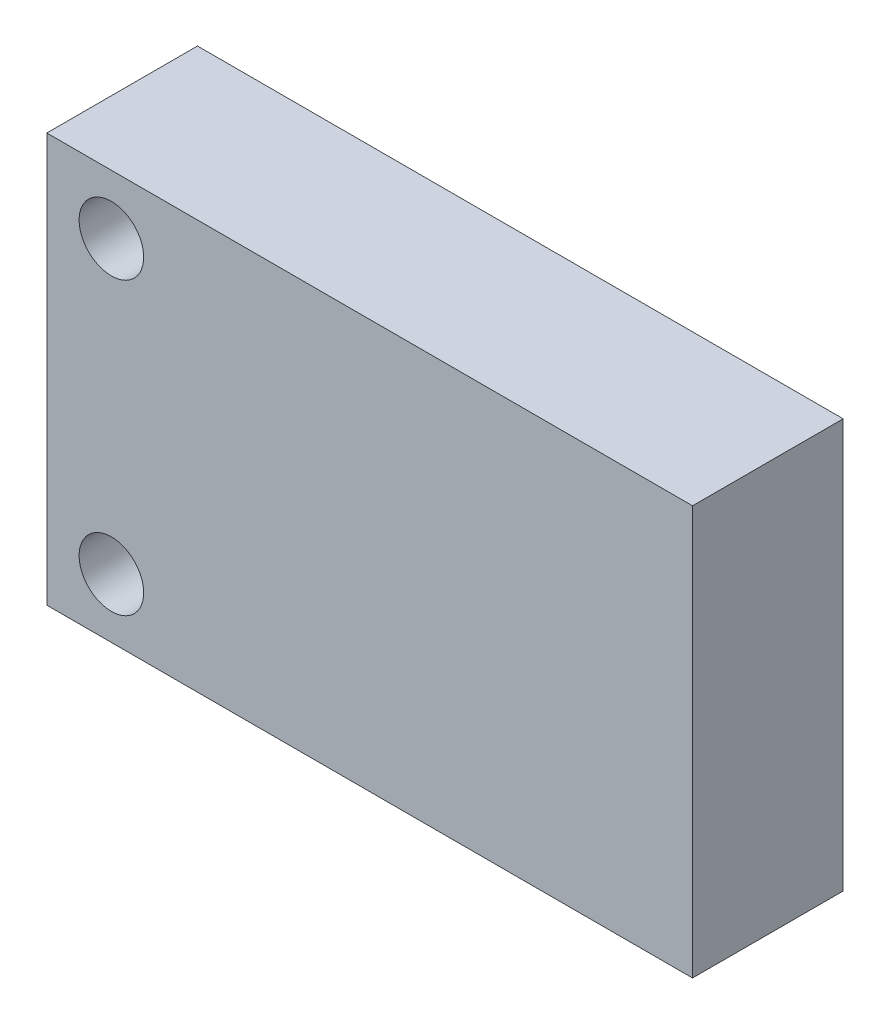
SolidWorks part; units mm, degrees
ref_plane "Ebene vorne" through (0, 0, 0) normal (0, 0, 1) x (1, 0, 0)
ref_plane "Ebene oben" through (0, 0, 0) normal (0, 1, 0) x (1, 0, 0)
ref_plane "Ebene rechts" through (0, 0, 0) normal (1, 0, 0) x (0, 0, -1)
sketch "Skizze1" plane through (0, 0, 0) normal (0, 0, 1) x (1, 0, 0)
  line L1 (-15, 9.5) -> (15, 9.5)
  line L2 (-15, 9.5) -> (-15, -9.5)
  line L3 (-15, -9.5) -> (15, -9.5)
  line L4 (15, 9.5) -> (15, -9.5)
  line L5 (-15, 9.5) -> (15, -9.5) construction
  line L6 (-15, -9.5) -> (15, 9.5) construction
  point P0 (0, 0)
  dimension "D1" = 19
  dimension "D2" = 30
extrude "Aufsatz-Linear austragen1" add sketch "Skizze1" along normal blind 7
sketch "Skizze2" plane through (0, 0, 7) normal (0, 0, 1) x (1, 0, 0)
  line L0 (-15, 9.5) -> (-15, -9.5) construction
  line L1 (12, -6.75) -> (-12, -6.75) construction
  line L2 (12, -6.75) -> (12, 6.75) construction
  line L3 (12, 6.75) -> (-12, 6.75) construction
  line L4 (-12, -6.75) -> (-12, 6.75) construction
  line L5 (12, -6.75) -> (-12, 6.75) construction
  line L6 (12, 6.75) -> (-12, -6.75) construction
  circle A0 centre (-12, 6.75) radius 1.5
  circle A1 centre (-12, -6.75) radius 1.5
  point P0 (0, 0)
  dimension "D1" = 3
  dimension "D2" = 13.5
  dimension "D3" = 3
extrude "Schnitt-Linear austragen1" cut sketch "Skizze2" against normal through all
